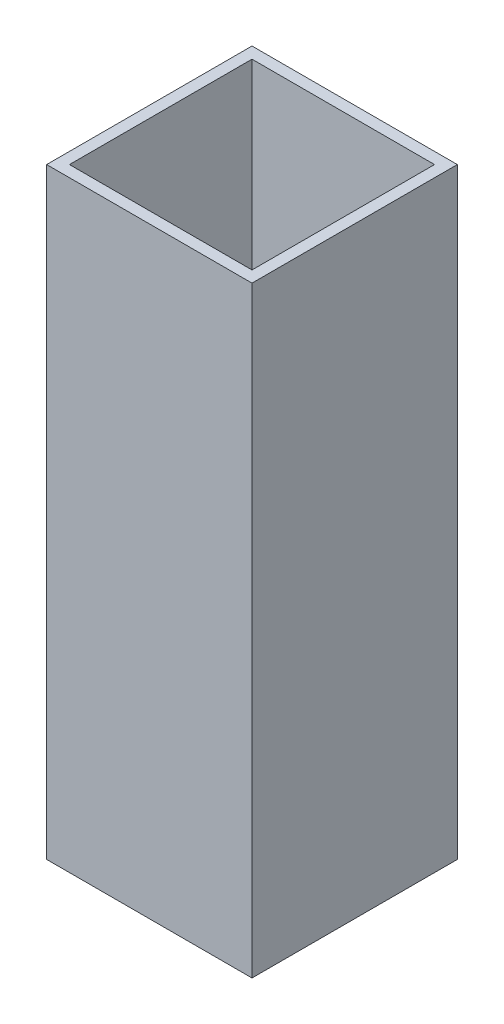
SolidWorks part; units mm, degrees
ref_plane "Front Plane" through (0, 0, 0) normal (0, 0, 1) x (1, 0, 0)
ref_plane "Top Plane" through (0, 0, 0) normal (0, 1, 0) x (1, 0, 0)
ref_plane "Right Plane" through (0, 0, 0) normal (1, 0, 0) x (0, 0, -1)
sketch "Sketch1" plane through (0, 0, 0) normal (0, 1, 0) x (1, 0, 0)
  line L1 (-77.0445, 48.0093) -> (-45.0445, 48.0093)
  line L2 (-77.0445, 48.0093) -> (-77.0445, 16.0093)
  line L3 (-77.0445, 16.0093) -> (-45.0445, 16.0093)
  line L4 (-45.0445, 48.0093) -> (-45.0445, 16.0093)
  line L5 (-79.0445, 50.0093) -> (-43.0445, 50.0093)
  line L6 (-79.0445, 50.0093) -> (-79.0445, 14.0093)
  line L7 (-79.0445, 14.0093) -> (-43.0445, 14.0093)
  line L8 (-43.0445, 50.0093) -> (-43.0445, 14.0093)
  dimension "D1" = 32
  dimension "D2" = 32
  dimension "D3" = 2
  dimension "D4" = 2
  dimension "D5" = 2
  dimension "D6" = 2
extrude "Boss-Extrude1" add sketch "Sketch1" along normal blind 10
sketch "Sketch2" plane through (0, 0, 0) normal (0, -1, 0) x (1, 0, 0)
  line L1 (-43.0445, -14.0093) -> (-79.0445, -14.0093)
  line L2 (-43.0445, -14.0093) -> (-43.0445, -50.0093)
  line L3 (-43.0445, -50.0093) -> (-79.0445, -50.0093)
  line L4 (-79.0445, -14.0093) -> (-79.0445, -50.0093)
  line L5 (-75.0445, -18.0093) -> (-47.0445, -18.0093)
  line L6 (-75.0445, -18.0093) -> (-75.0445, -46.0093)
  line L7 (-75.0445, -46.0093) -> (-47.0445, -46.0093)
  line L8 (-47.0445, -18.0093) -> (-47.0445, -46.0093)
  dimension "D1" = 4
  dimension "D2" = 4
  dimension "D3" = 4
  dimension "D4" = 4
sketch "Sketch5" plane through (0, 10, 0) normal (0, 1, 0) x (1, 0, 0)
  line L1 (-79.0445, 50.0093) -> (-43.0445, 50.0093)
  line L2 (-79.0445, 50.0093) -> (-79.0445, 14.0093)
  line L3 (-79.0445, 14.0093) -> (-43.0445, 14.0093)
  line L4 (-43.0445, 50.0093) -> (-43.0445, 14.0093)
  line L10 (-77.0445, 48.0093) -> (-77.0445, 16.0093) construction
  line L11 (-43.0445, 14.0093) -> (-79.0445, 14.0093)
  line L12 (-43.0445, 14.0093) -> (-43.0445, 50.0093)
  line L13 (-43.0445, 50.0093) -> (-79.0445, 50.0093)
  line L14 (-79.0445, 14.0093) -> (-79.0445, 50.0093)
  line L15 (-77.0445, 16.0093) -> (-45.0445, 16.0093) construction
  line L16 (-45.0445, 48.0093) -> (-77.0445, 48.0093) construction
  line M5 (-45.0445, 16.0093) -> (-77.0445, 16.0093)
  line M6 (-77.0445, 16.0093) -> (-77.0445, 48.0093)
  line M7 (-77.0445, 48.0093) -> (-45.0445, 48.0093)
  line M8 (-45.0445, 48.0093) -> (-45.0445, 16.0093)
  dimension "D3" = 2
  dimension "D4" = 2
  dimension "D1" = 2
  dimension "D2" = 2
extrude "Boss-Extrude5" add sketch "Sketch5" along normal blind 63.5 contours L14 L11 L12 L13 M8 M5 M6 M7
extrude "Boss-Extrude9" add sketch "Sketch2" along normal blind 2
sketch "Sketch9" plane through (0, -2, 0) normal (0, -1, 0) x (1, 0, 0)
  line L1 (-79.0445, -14.0093) -> (-43.0445, -14.0093)
  line L2 (-79.0445, -14.0093) -> (-79.0445, -50.0093)
  line L3 (-79.0445, -50.0093) -> (-43.0445, -50.0093)
  line L4 (-43.0445, -14.0093) -> (-43.0445, -50.0093)
  line L5 (-77.0445, -16.0093) -> (-45.0445, -16.0093)
  line L6 (-77.0445, -16.0093) -> (-77.0445, -48.0093)
  line L7 (-77.0445, -48.0093) -> (-45.0445, -48.0093)
  line L8 (-45.0445, -16.0093) -> (-45.0445, -48.0093)
  dimension "D3" = 2
  dimension "D4" = 2
  dimension "D1" = 2
  dimension "D2" = 2
extrude "Boss-Extrude11" add sketch "Sketch9" along normal blind 30
equation "\"tolerance\"= 2"
equation "\"length\"= 30"
equation "\"D1@Sketch1\"=\"length\"+\"tolerance\""
equation "\"D2@Sketch1\"=\"length\"+\"tolerance\""
equation "\"protrusion_thickness\"= 2"
equation "\"D3@Sketch1\"=\"protrusion_thickness\""
equation "\"D4@Sketch1\"=\"protrusion_thickness\""
equation "\"D5@Sketch1\"=\"protrusion_thickness\""
equation "\"locking protrusion thickness\"=2"
equation "\"D1@Sketch2\"=\"protrusion_thickness\"+\"locking protrusion thickness\""
equation "\"D2@Sketch2\"=\"D1@Sketch2\""
equation "\"D3@Sketch2\"=\"D1@Sketch2\""
equation "\"D4@Sketch2\"=\"D1@Sketch2\""
equation "\"D1@Boss-Extrude1\"=10"
equation "\"D1@Sketch5\"=\"locking protrusion thickness\""
equation "\"D2@Sketch5\"=\"locking protrusion thickness\""
equation "\"D3@Sketch5\"=\"locking protrusion thickness\""
equation "\"D4@Sketch5\"=\"locking protrusion thickness\""
equation "\"D1@Sketch9\"=\"locking protrusion thickness\""
equation "\"D2@Sketch9\"=\"locking protrusion thickness\""
equation "\"D3@Sketch9\"=\"locking protrusion thickness\""
equation "\"D4@Sketch9\"=\"locking protrusion thickness\""
equation "\"D1@Boss-Extrude5\"=2.5*25.4"
